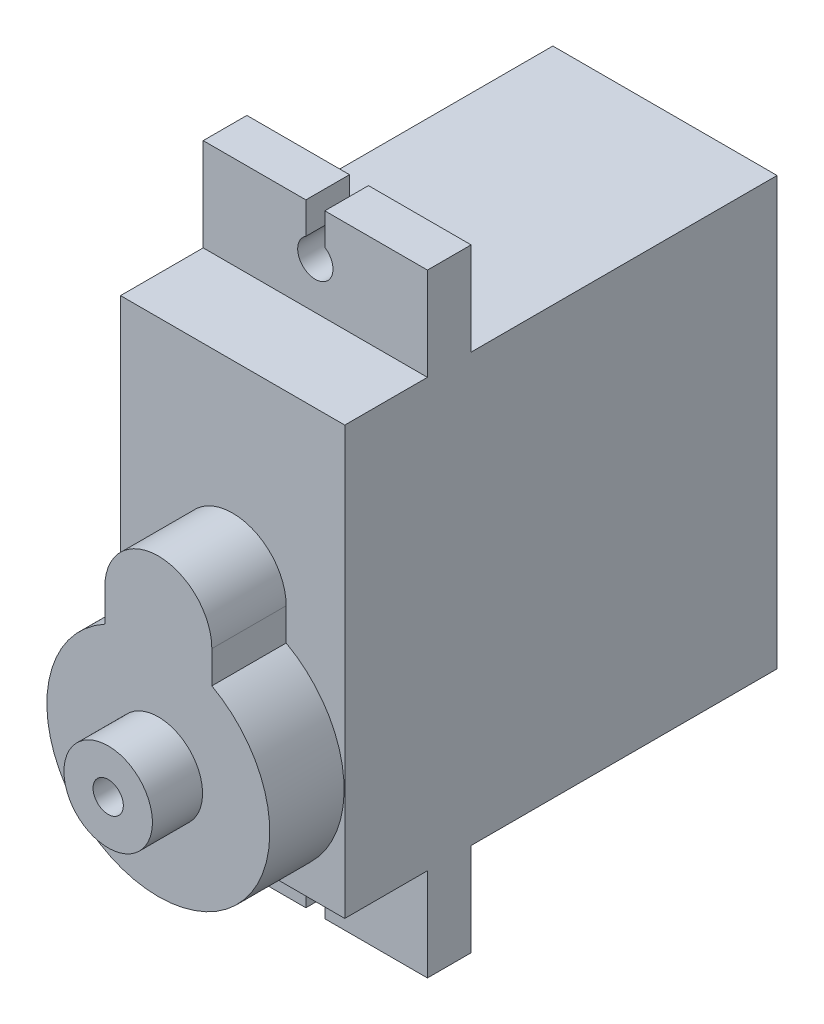
SolidWorks part; units mm, degrees
ref_plane "Front" through (0, 0, 0) normal (0, 0, 1) x (1, 0, 0)
ref_plane "Top" through (0, 0, 0) normal (0, 1, 0) x (1, 0, 0)
ref_plane "Right" through (0, 0, 0) normal (1, 0, 0) x (0, 0, -1)
sketch "Sketch1" plane through (0, 0, 0) normal (0, 1, 0) x (1, 0, 0)
  line L0 (0, 0) -> (12.07, 0)
  line L1 (12.07, 0) -> (12.07, 23.27)
  line L2 (12.07, 23.27) -> (0, 23.27)
  line L3 (0, 23.27) -> (0, 0)
  dimension "D1" = 23.27
  dimension "D2" = 12.07
extrude "Boss-Extrude1" add sketch "Sketch1" along normal blind 23
sketch "Sketch2" plane through (0, 0, 0) normal (0, 0, 1) x (1, 0, 0)
  line L0 (6.035, 23) -> (6.035, 0) construction
  line L1 (0, 23) -> (12.07, 23) construction
  line L2 (0, 0) -> (12.07, 0) construction
  circle A0 centre (6.035, 6) radius 6
  dimension "D1" = 12
  dimension "D2" = 6
extrude "Boss-Extrude3" add sketch "Sketch2" along normal blind 4
sketch "Sketch4" plane through (0, 0, 0) normal (0, 0, 1) x (1, 0, 0)
  line L0 (6.035, 11.6371) -> (6.035, 23) construction
  line L1 (0, 23) -> (12.07, 23) construction
  line L2 (0, 15.88) -> (12.07, 15.88) construction
  line L3 (0, 23) -> (0, 0) construction
  line L4 (12.07, 23) -> (12.07, 0) construction
  line L5 (3.155, 13) -> (3.155, 11.2636)
  line L6 (3.155, 11.2636) -> (8.915, 11.2636)
  line L7 (8.915, 11.2636) -> (8.915, 13)
  circle A0 centre (6.035, 6) radius 6 construction
  arc A1 (8.915, 13) -> (3.155, 13) centre (6.035, 13) ccw
  circle A2 centre (6.035, 6) radius 6 construction
  dimension "D2" = 5.76
  dimension "D1" = 4.2429
extrude "Boss-Extrude4" add sketch "Sketch4" along normal blind 4
sketch "Sketch6" plane through (0, 0, 0) normal (0, -1, 0) x (1, 0, 0)
  line L0 (0, -4.45) -> (12.07, -4.45)
  line L1 (0, -23.27) -> (0, 0) construction
  line L2 (12.07, 0) -> (12.07, -23.27) construction
  line L3 (12.07, -4.45) -> (12.07, -6.8)
  line L4 (12.07, -6.8) -> (0, -6.8)
  line L5 (0, -6.8) -> (0, -4.45)
  line L6 (0, 0) -> (6.035, 0) construction
  dimension "D1" = 2.35
  dimension "D2" = 4.45
extrude "Boss-Extrude5" add sketch "Sketch6" along normal blind 5
sketch "Sketch7" plane through (0, 23, 0) normal (0, 1, 0) x (-1, 0, 0)
  line L0 (0, -6.8) -> (-12.07, -6.8)
  line L1 (0, -23.27) -> (0, 0) construction
  line L2 (-12.07, 0) -> (-12.07, -23.27) construction
  line L3 (-12.07, -6.8) -> (-12.07, -4.45)
  line L4 (-12.07, -4.45) -> (0, -4.45)
  line L5 (0, -4.45) -> (0, -6.8)
  line L6 (-6.035, 0) -> (-12.035, 0) construction
  point P7 (-9.035, 0)
  dimension "D1" = 2.35
  dimension "D2" = 4.45
extrude "Boss-Extrude6" add sketch "Sketch7" along normal blind 5
sketch "Sketch8" plane through (0, 0, -4.45) normal (0, 0, 1) x (1, 0, 0)
  line L0 (6.035, -5) -> (6.035, 28) construction
  line L1 (12.07, -5) -> (0, -5) construction
  line L2 (0, 28) -> (12.07, 28) construction
  line L3 (0, 23) -> (12.07, 28) construction
  line L4 (6.035, 11.5) -> (12.07, 11.5) construction
  line L5 (12.07, 23) -> (12.07, 0) construction
  line L6 (0, -5) -> (12.07, 0) construction
  circle A0 centre (6.035, 25.5) radius 0.95
  circle A1 centre (6.035, -2.5) radius 0.95
  dimension "D1" = 1.9
extrude "Cut-Extrude1" cut sketch "Sketch8" against normal through all
sketch "Sketch9" plane through (0, 0, -4.45) normal (0, 0, 1) x (1, 0, 0)
  line L0 (6.035, 28) -> (6.035, 25.5) construction
  line L1 (0, 28) -> (12.07, 28) construction
  line L2 (12.07, -5) -> (0, -5) construction
  line L3 (5.525, 28) -> (5.525, 25.5)
  line L4 (6.545, 28) -> (6.545, 25.5)
  line L5 (5.525, 25.5) -> (6.545, 25.5)
  line L6 (5.525, -2.5) -> (6.545, -2.5)
  line L7 (5.525, -2.5) -> (5.525, -5)
  line L8 (5.525, 28) -> (5.525, -5) construction
  line L9 (6.035, -2.5) -> (6.035, -5) construction
  line L10 (6.035, 28) -> (6.035, -5) construction
  line L11 (6.545, -2.5) -> (6.545, -5)
  line L12 (6.545, 28) -> (6.545, -5) construction
  line L13 (5.525, -5) -> (6.545, -5)
  line L14 (5.525, 28) -> (6.545, 28)
  dimension "D1" = 0.51
  dimension "D2" = 0.51
extrude "Cut-Extrude2" cut sketch "Sketch9" against normal through all
sketch "Sketch10" plane through (0, 0, 4) normal (0, 0, 1) x (1, 0, 0)
  circle A0 centre (6.035, 6) radius 2.38
  circle A1 centre (6.035, 6) radius 0.815
  dimension "D1" = 4.76
  dimension "D2" = 1.63
extrude "Boss-Extrude7" add sketch "Sketch10" along normal blind 2.7
